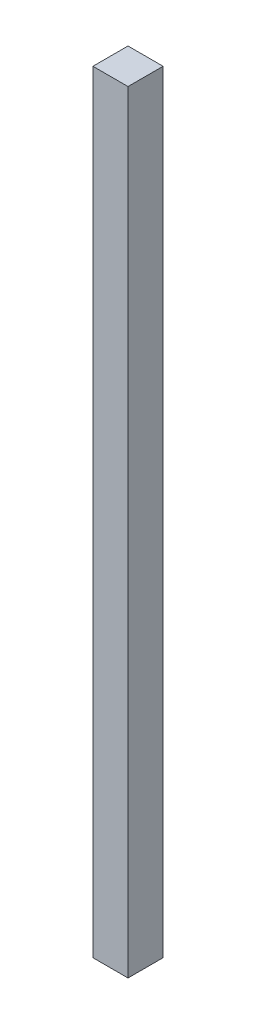
SolidWorks part; units mm, degrees
ref_plane "Front Plane" through (0, 0, 0) normal (0, 0, 1) x (1, 0, 0)
ref_plane "Top Plane" through (0, 0, 0) normal (0, 1, 0) x (1, 0, 0)
ref_plane "Right Plane" through (0, 0, 0) normal (1, 0, 0) x (0, 0, -1)
sketch "Sketch1" plane through (0, 0, 0) normal (0, 1, 0) x (1, 0, 0)
  line L1 (-50, -50) -> (50, -50)
  line L2 (-50, -50) -> (-50, 50)
  line L3 (-50, 50) -> (50, 50)
  line L4 (50, -50) -> (50, 50)
  line L5 (-50, -50) -> (50, 50) construction
  line L6 (-50, 50) -> (50, -50) construction
  point P0 (0, 0)
  dimension "D1" = 100
  dimension "D2" = 100
extrude "Boss-Extrude1" add sketch "Sketch1" along normal blind 2200
shell "Shell1" thickness 3
sketch "Sketch3" plane through (0, 0, -50) normal (0, 0, -1) x (-1, 0, 0)
  line L0 (0, 2200) -> (0, 0) construction
  line L1 (-50, 2200) -> (50, 2200) construction
  line L2 (0, 350) -> (0, 1850) construction
  line L3 (-25, 350) -> (-25, 1850)
  line L4 (25, 350) -> (25, 1850)
  arc A0 (-25, 350) -> (25, 350) centre (0, 350) ccw
  arc A1 (25, 1850) -> (-25, 1850) centre (0, 1850) ccw
  point P7 (0, 1100)
  dimension "D2" = 25
  dimension "D1" = 1500
extrude "Cut-Extrude2" cut sketch "Sketch3" against normal blind 10
